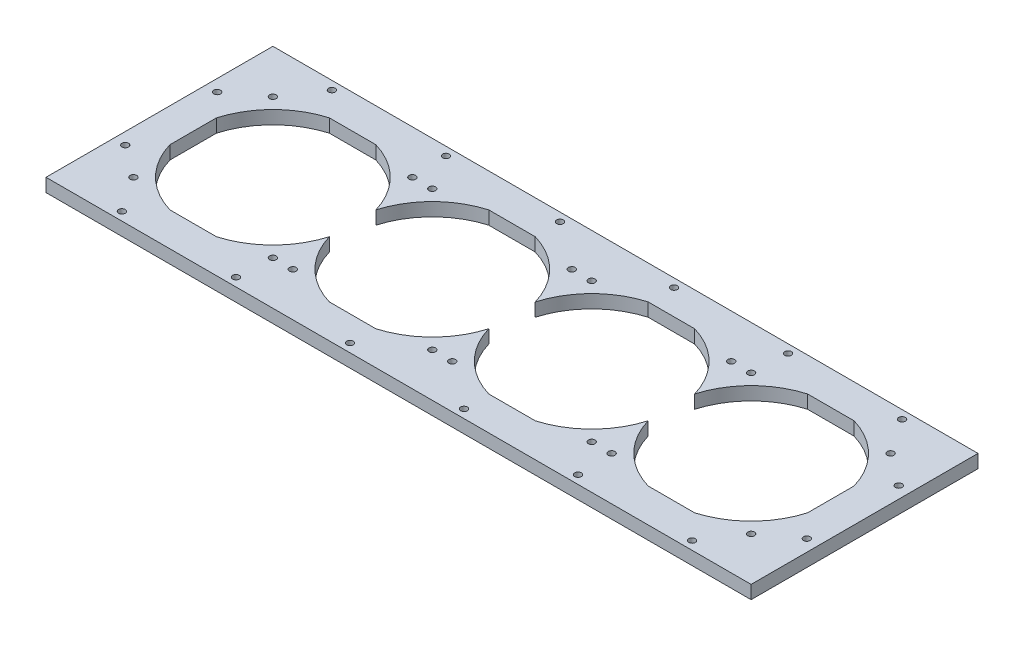
SolidWorks part; units mm, degrees
ref_plane "Front Plane" through (0, 0, 0) normal (0, 0, 1) x (1, 0, 0)
ref_plane "Top Plane" through (0, 0, 0) normal (0, 1, 0) x (1, 0, 0)
ref_plane "Right Plane" through (0, 0, 0) normal (1, 0, 0) x (0, 0, -1)
sketch "Sketch1" plane through (0, 0, 0) normal (0, 1, 0) x (1, 0, 0)
  line L0 (43.8449, 182.959) -> (43.8449, -49.9293) construction
  line L1 (-41.5551, 155.7636) -> (489.2449, 155.7636)
  line L2 (-41.5551, 155.7636) -> (-41.5551, -15.0364)
  line L3 (-41.5551, -15.0364) -> (489.2449, -15.0364)
  line L4 (489.2449, 155.7636) -> (489.2449, -15.0364)
  line L5 (132.4481, 70.3636) -> (-99.5215, 70.3636) construction
  line L6 (223.8449, 87.8636) -> (223.8449, 52.8636) construction
  line L7 (146.3449, 130.3636) -> (181.3449, 130.3636)
  line L8 (26.3449, 130.3636) -> (61.3449, 130.3636)
  line L9 (-16.1551, 87.8636) -> (-16.1551, 52.8636)
  line L10 (26.3449, 10.3636) -> (61.3449, 10.3636)
  line L13 (146.3449, 10.3636) -> (181.3449, 10.3636)
  line L15 (266.3449, 130.3636) -> (301.3449, 130.3636)
  line L17 (266.3449, 10.3636) -> (301.3449, 10.3636)
  line L19 (386.3449, 130.3636) -> (421.3449, 130.3636)
  line L20 (463.8449, 87.8636) -> (463.8449, 52.8636)
  line L21 (386.3449, 10.3636) -> (421.3449, 10.3636)
  line L23 (103.8449, 70.3636) -> (103.8449, 52.8636) [skipped]
  line L24 (343.8449, 87.8636) -> (343.8449, 52.8636) [skipped]
  line L25 (223.8449, 87.8636) -> (223.8449, 52.8636) [skipped]
  arc A0 (103.8449, 87.8636) -> (61.3449, 130.3636) centre (43.8449, 70.3636) ccw
  circle A1 centre (-8.6551, 17.8636) radius 2.5
  circle A2 centre (96.3449, 17.8636) radius 2.5
  circle A3 centre (96.3449, 122.8636) radius 2.5
  circle A4 centre (-8.6551, 122.8636) radius 2.5
  arc A5 (146.3449, 130.3636) -> (103.8449, 87.8636) centre (163.8449, 70.3636) ccw
  circle A6 centre (111.3449, 17.8636) radius 2.5
  circle A7 centre (216.3449, 17.8636) radius 2.5
  circle A8 centre (111.3449, 122.8636) radius 2.5
  circle A9 centre (216.3449, 122.8636) radius 2.5
  arc A10 (223.8449, 87.8636) -> (181.3449, 130.3636) centre (163.8449, 70.3636) ccw
  circle A11 centre (231.3449, 17.8636) radius 2.5
  circle A12 centre (336.3449, 17.8636) radius 2.5
  circle A13 centre (231.3449, 122.8636) radius 2.5
  circle A14 centre (336.3449, 122.8636) radius 2.5
  circle A16 centre (351.3449, 17.8636) radius 2.5
  circle A17 centre (456.3449, 17.8636) radius 2.5
  circle A18 centre (351.3449, 122.8636) radius 2.5
  circle A19 centre (456.3449, 122.8636) radius 2.5
  arc A21 (103.8449, 52.8636) -> (146.3449, 10.3636) centre (163.8449, 70.3636) ccw
  circle A22 centre (9.2449, 149.4136) radius 2.5
  circle A23 centre (95.0849, 149.4136) radius 2.5
  circle A24 centre (180.9249, 149.4136) radius 2.5
  circle A25 centre (266.7649, 149.4136) radius 2.5
  circle A26 centre (352.6049, 149.4136) radius 2.5
  circle A27 centre (438.4449, 149.4136) radius 2.5
  circle A28 centre (480.3847, 35.7636) radius 2.5
  circle A29 centre (438.4449, -8.6864) radius 2.5
  circle A30 centre (352.6049, -8.6864) radius 2.5
  circle A31 centre (266.7649, -8.6864) radius 2.5
  circle A32 centre (180.9249, -8.6864) radius 2.5
  circle A33 centre (95.0849, -8.6864) radius 2.5
  circle A34 centre (9.2449, -8.6864) radius 2.5
  circle A35 centre (480.3847, 104.9636) radius 2.5
  circle A36 centre (-32.6949, 35.7636) radius 2.5
  circle A37 centre (-32.6949, 104.9636) radius 2.5
  arc A38 (26.3449, 130.3636) -> (-16.1551, 87.8636) centre (43.8449, 70.3636) ccw
  arc A39 (-16.1551, 52.8636) -> (26.3449, 10.3636) centre (43.8449, 70.3636) ccw
  arc A40 (61.3449, 10.3636) -> (103.8449, 52.8636) centre (43.8449, 70.3636) ccw
  arc A41 (223.8449, 87.8636) -> (103.8449, 87.8636) centre (163.8449, 70.3636) ccw [skipped]
  arc A42 (343.8449, 87.8636) -> (223.8449, 87.8636) centre (283.8449, 70.3636) ccw [skipped]
  arc A43 (343.8449, 52.8636) -> (343.8449, 87.8636) centre (403.8449, 70.3636) ccw [skipped]
  arc A44 (266.3449, 130.3636) -> (223.8449, 87.8636) centre (283.8449, 70.3636) ccw
  arc A45 (343.8449, 87.8636) -> (301.3449, 130.3636) centre (283.8449, 70.3636) ccw
  arc A46 (301.3449, 10.3636) -> (343.8449, 52.8636) centre (283.8449, 70.3636) ccw
  arc A47 (223.8449, 52.8636) -> (266.3449, 10.3636) centre (283.8449, 70.3636) ccw
  arc A48 (386.3449, 130.3636) -> (343.8449, 87.8636) centre (403.8449, 70.3636) ccw
  arc A49 (463.8449, 87.8636) -> (421.3449, 130.3636) centre (403.8449, 70.3636) ccw
  arc A50 (421.3449, 10.3636) -> (463.8449, 52.8636) centre (403.8449, 70.3636) ccw
  arc A51 (343.8449, 52.8636) -> (386.3449, 10.3636) centre (403.8449, 70.3636) ccw
  arc A52 (181.3449, 10.3636) -> (223.8449, 52.8636) centre (163.8449, 70.3636) ccw
  arc A53 (181.3449, 10.3636) -> (223.8449, 52.8636) centre (163.8449, 70.3636) ccw [skipped]
  arc A54 (103.8449, 52.8636) -> (146.3449, 10.3636) centre (163.8449, 70.3636) ccw [skipped]
  dimension "D3" = 125
  dimension "D4" = 85.4
  dimension "D7" = 105
  dimension "D8" = 5
  dimension "D10" = 5
  dimension "D11" = 6.35
  dimension "D12" = 50.8
  dimension "D14" = 5
  dimension "D15" = 50.8
  dimension "D1" = 170.8
  dimension "D2" = 530.8
  dimension "D5" = 85.4
  dimension "D6" = 105
  dimension "D17" = 120
  dimension "D18" = 4
  dimension "D20" = 60
  dimension "D9" = 4
  dimension "D13" = 6
  dimension "D16" = 2
extrude "Boss-Extrude1" add sketch "Sketch1" along normal blind 10
